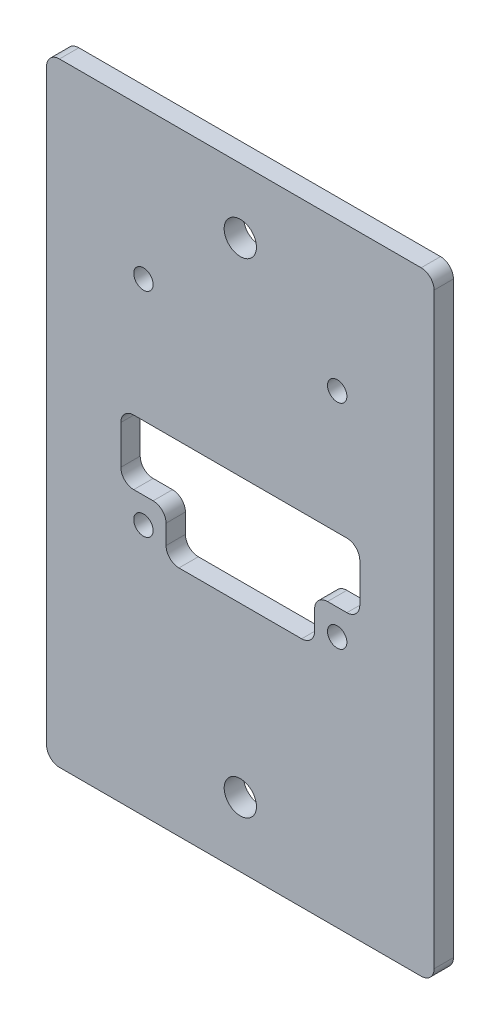
SolidWorks part; units mm, degrees
ref_plane "Front Plane" through (0, 0, 0) normal (0, 0, 1) x (1, 0, 0)
ref_plane "Top Plane" through (0, 0, 0) normal (0, 1, 0) x (1, 0, 0)
ref_plane "Right Plane" through (0, 0, 0) normal (1, 0, 0) x (0, 0, -1)
sketch "Sketch1" plane through (0, 0, 0) normal (0, 0, 1) x (1, 0, 0)
  line L0 (-30, 27.5) -> (30, 27.5) construction
  line L1 (-28, -47.5) -> (28, -47.5)
  line L2 (-30, -45.5) -> (-30, 45.5)
  line L3 (-28, 47.5) -> (28, 47.5)
  line L4 (30, -45.5) -> (30, 45.5)
  line L5 (-30, -47.5) -> (30, 47.5) construction
  line L6 (-30, 47.5) -> (30, -47.5) construction
  line L7 (-30, -17.5) -> (30, -17.5) construction
  line L8 (-15, 24.5) -> (15, 24.5) construction
  line L9 (-11.5, -9.5) -> (-11.5, -6.5)
  line L10 (-9.5, -11.5) -> (9.5, -11.5)
  line L11 (-18.5, -2.5) -> (-18.5, 3.5)
  line L12 (-16.5, 5.5) -> (16.5, 5.5)
  line L13 (18.5, -2.5) -> (18.5, 3.5)
  line L14 (-18.5, -11.5) -> (18.5, 5.5) construction
  line L15 (-18.5, 5.5) -> (18.5, -11.5) construction
  line L16 (-13.5, -4.5) -> (-16.5, -4.5)
  line L17 (11.5, -9.5) -> (11.5, -6.5)
  line L18 (13.5, -4.5) -> (16.5, -4.5)
  circle A0 centre (0, 37.5) radius 2.5
  circle A1 centre (0, -37.5) radius 2.5
  circle A2 centre (-15, 24.5) radius 1.5
  circle A3 centre (15, 24.5) radius 1.5
  circle A4 centre (-15, -8.5) radius 1.5
  circle A5 centre (15, -8.5) radius 1.5
  arc A6 (-16.5, -4.5) -> (-18.5, -2.5) centre (-16.5, -2.5) cw
  arc A7 (-11.5, -6.5) -> (-13.5, -4.5) centre (-13.5, -6.5) ccw
  arc A8 (-11.5, -9.5) -> (-9.5, -11.5) centre (-9.5, -9.5) ccw
  arc A9 (11.5, -9.5) -> (9.5, -11.5) centre (9.5, -9.5) cw
  arc A10 (13.5, -4.5) -> (11.5, -6.5) centre (13.5, -6.5) ccw
  arc A11 (16.5, -4.5) -> (18.5, -2.5) centre (16.5, -2.5) ccw
  arc A12 (16.5, 5.5) -> (18.5, 3.5) centre (16.5, 3.5) cw
  arc A13 (-18.5, 3.5) -> (-16.5, 5.5) centre (-16.5, 3.5) cw
  arc A14 (-28, -47.5) -> (-30, -45.5) centre (-28, -45.5) cw
  arc A15 (28, -47.5) -> (30, -45.5) centre (28, -45.5) ccw
  arc A16 (28, 47.5) -> (30, 45.5) centre (28, 45.5) cw
  arc A17 (-30, 45.5) -> (-28, 47.5) centre (-28, 45.5) cw
  point P0 (0, 0)
  point P13 (0, 47.5)
  point P19 (0, 24.5)
  point P20 (0, 27.5)
  point P22 (0, -3)
  point P38 (-18.5, -4.5)
  point P41 (-11.5, -4.5)
  point P48 (11.5, -4.5)
  point P51 (18.5, -4.5)
  dimension "D5" = 5
  dimension "D8" = 3
  dimension "D20" = 2
  dimension "D21" = 2
  dimension "D1" = 60
  dimension "D2" = 95
  dimension "D3" = 20
  dimension "D4" = 45
  dimension "D6" = 10
  dimension "D7" = 10
  dimension "D9" = 30
  dimension "D10" = 3
  dimension "D12" = 17
  dimension "D13" = 37
  dimension "D14" = 3
  dimension "D15" = 33
  dimension "D16" = 7
  dimension "D17" = 7
  dimension "D18" = 7
  dimension "D19" = 7
  dimension "D11" = 2
extrude "Boss-Extrude1" add sketch "Sketch1" along normal blind 3
